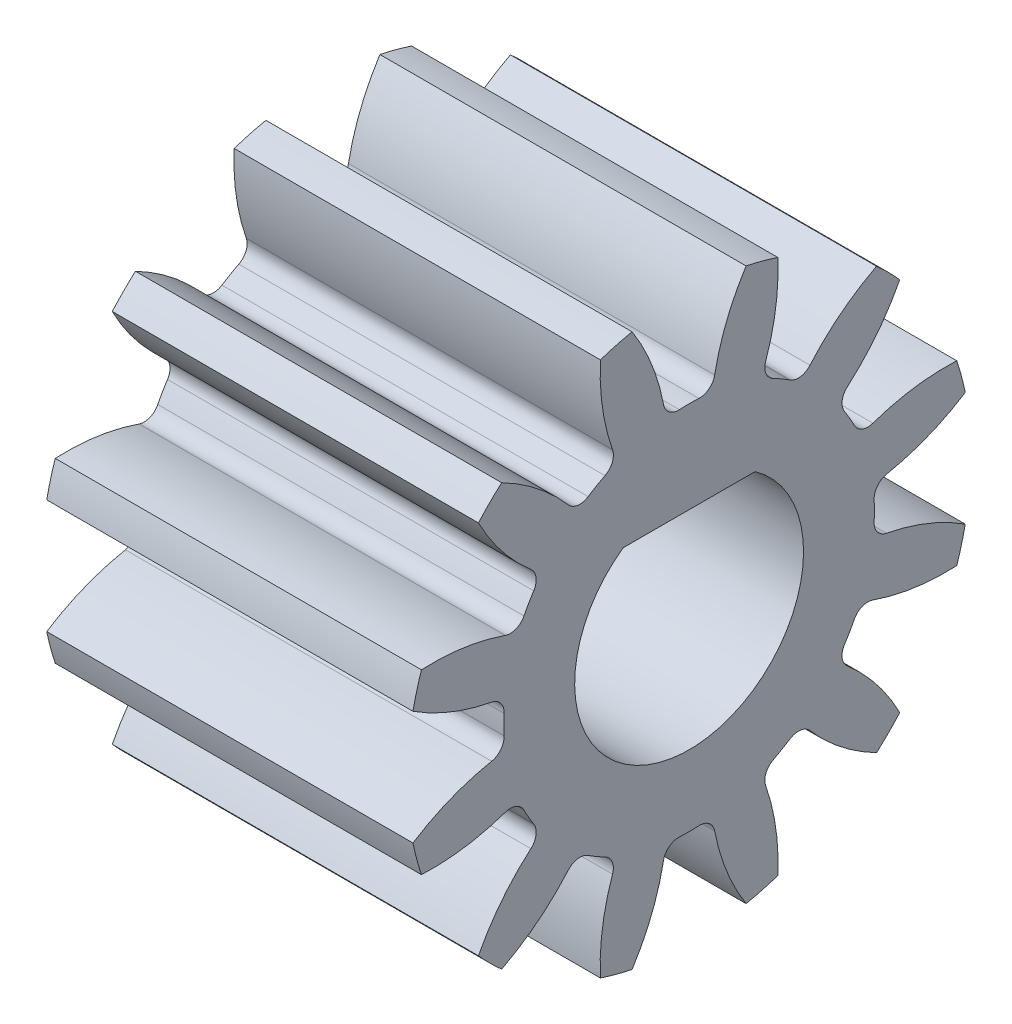
SolidWorks part; units mm, degrees
ref_plane "Front Plane" through (0, 0, 0) normal (0, 0, 1) x (1, 0, 0)
ref_plane "Top Plane" through (0, 0, 0) normal (0, 1, 0) x (1, 0, 0)
ref_plane "Right Plane" through (0, 0, 0) normal (1, 0, 0) x (0, 0, -1)
sketch "Sketch1" plane through (0, 0, 0) normal (1, 0, 0) x (0, 0, -1)
  circle A0 centre (0, 0) radius 3.125
  circle A1 centre (0, 0) radius 7.7
  dimension "D1" = 6.25
  dimension "D2" = 15.4
extrude "Boss-Extrude2" add sketch "Sketch1" along normal blind 10
sketch "Sketch3" plane through (10, 0, 0) normal (1, 0, 0) x (0, 0, -1)
  line L0 (0, 0) -> (0, 7.7) construction
  line L1 (-0.639, 5.0195) -> (0, 0) construction
  line L2 (0, 3.702) -> (-4.9814, 17.3883) construction
  circle A0 centre (0, 0) radius 7.7 construction
  arc A1 (0.639, 5.0195) -> (-0.639, 5.0195) centre (0, 0) ccw
  arc A2 (1.0289, 6.5193) -> (-1.0289, 6.5193) centre (0, 0) ccw construction
  arc A3 (1.5567, 7.541) -> (-1.5567, 7.541) centre (0, 0) ccw
  arc A4 (-1.5567, 7.541) -> (-0.639, 5.0195) centre (-6.6717, 4.2515) cw
  arc A5 (1.5567, 7.541) -> (0.639, 5.0195) centre (6.6717, 4.2515) ccw
  point P17 (-0.957, 6.3315)
  dimension "D1" = 15.4
  dimension "D2" = 13.2
  dimension "D3" = 2.64
  dimension "D4" = 20
  dimension "D5" = 2.0579
extrude "Cut-Extrude1" cut sketch "Sketch3" against normal through all
fillet "Fillet1" radius 0.418 2 edges at (5, 5.0195, -0.639) (5, 5.0195, 0.639)
pattern_circular "CirPattern2" count 12 over 360 about axis through (0, 0, 0) along (1, 0, 0) of "Fillet1", "Cut-Extrude1"
sketch "Sketch4" plane through (0, 0, 0) normal (-1, 0, 0) x (0, 0, 1)
  line L0 (1.2919, -2.8455) -> (3, -2.8455) construction
  line L5 (-1.8, 2.5545) -> (1.8, 2.5545)
  circle A0 centre (0, 0) radius 3.125 construction
  arc A1 (-1.8, 2.5545) -> (1.8, 2.5545) centre (0, 0.1545) cw
  dimension "D2" = 3
  dimension "D1" = 5.4
  dimension "D3" = 3.6
extrude "Boss-Extrude3" add sketch "Sketch4" against normal blind 10
equation "\"No of teeth\"= 12"
equation "\"Module\"= 1.1"
equation "\"Outer Diameter\"= ( \"No of teeth\" + 2 ) * \"Module\""
equation "\"Pitch Diameter\"= \"No of teeth\" * \"Module\""
equation "\"Backlash\"= 0.3 * \"Module\""
equation "\"Arc Length\"= ( ( \"Module\" * pi ) / 2 ) + \"Backlash\""
equation "\"Fillet Radius\"= 0.38 * \"Module\""
equation "\"Bore Diameter\"= 6.25"
equation "\"Presseure angle\"= 20"
equation "\"Tooth Design\"= IIF ( \"Module\" <= 1.25 , 2.4 * \"Module\" , 2.25 * \"Module\" )"
equation "\"D1@Sketch1\"=\"Bore Diameter\""
equation "\"D2@Sketch1\"=\"Outer Diameter\""
equation "\"D1@Sketch3\"=\"Outer Diameter\""
equation "\"D2@Sketch3\"=\"Pitch Diameter\""
equation "\"D3@Sketch3\"=\"Tooth Design\""
equation "\"D4@Sketch3\"=\"Presseure angle\""
equation "\"D5@Sketch3\"=\"Arc Length\""
equation "\"D1@Fillet1\"=\"Fillet Radius\""
equation "\"D1@CirPattern2\"=\"No of teeth\""
